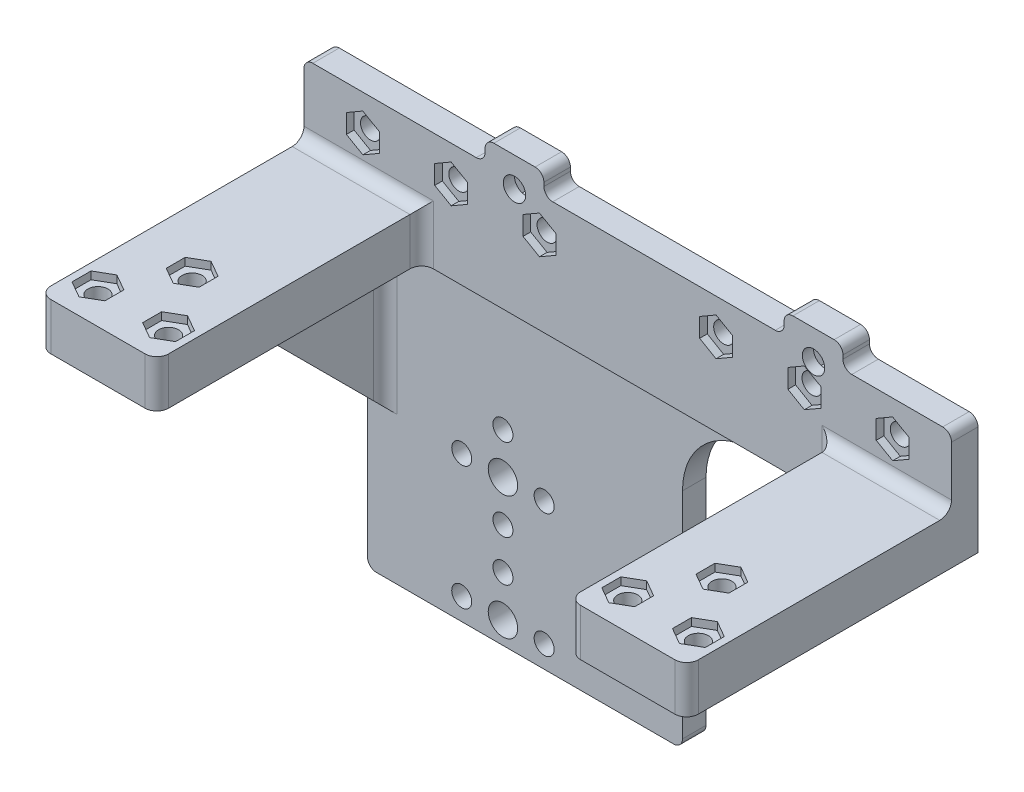
SolidWorks part; units mm, degrees
ref_plane "前视基准面" through (0, 0, 0) normal (0, 0, 1) x (1, 0, 0)
ref_plane "上视基准面" through (0, 0, 0) normal (0, 1, 0) x (1, 0, 0)
ref_plane "右视基准面" through (0, 0, 0) normal (1, 0, 0) x (0, 0, -1)
sketch "草图1" plane through (0, 0, 0) normal (0, 0, 1) x (1, 0, 0)
  line L6 (-55, 0) -> (55, 0)
  line L11 (55, 0) -> (55, 20)
  line L12 (55, 20) -> (-55, 20)
  line L13 (-55, 20) -> (-55, 0)
  line L14 (-45, 14) -> (45, 14) construction
  line L15 (0, 14) -> (0, 0) construction
  circle A6 centre (-45, 14) radius 1.7
  circle A7 centre (-30, 14) radius 1.7
  circle A8 centre (-15, 14) radius 1.7
  circle A9 centre (15, 14) radius 1.7
  circle A10 centre (30, 14) radius 1.7
  circle A11 centre (45, 14) radius 1.7
  dimension "D1" = 110
  dimension "D2" = 3.4
  dimension "D3" = 90
  dimension "D4" = 60
  dimension "D5" = 30
  dimension "D6" = 20
  dimension "D7" = 6
extrude "凸台-拉伸1" add sketch "草图1" along normal blind 4.5
sketch "草图2" plane through (0, 0, 4.5) normal (0, 0, 1) x (1, 0, 0)
  line L0 (0, 0) -> (0, 12.4325) construction
  line L1 (-55, 0) -> (-35, 0)
  line L2 (-55, 0) -> (-55, 8)
  line L3 (-55, 8) -> (-35, 8)
  line L4 (-35, 0) -> (-35, 8)
  line L5 (55, 0) -> (35, 0)
  line L6 (55, 0) -> (55, 8)
  line L7 (55, 8) -> (35, 8)
  line L8 (35, 0) -> (35, 8)
  dimension "D1" = 8
  dimension "D2" = 20
extrude "凸台-拉伸2" add sketch "草图2" along normal blind 45
sketch "草图3" plane through (0, 0, 4.5) normal (0, 0, 1) x (1, 0, 0)
  line L1 (-45, 17.22) -> (-47.7886, 15.61)
  line L2 (-47.7886, 15.61) -> (-47.7886, 12.39)
  line L3 (-47.7886, 12.39) -> (-45, 10.78)
  line L4 (-45, 10.78) -> (-42.2114, 12.39)
  line L5 (-42.2114, 12.39) -> (-42.2114, 15.61)
  line L6 (-42.2114, 15.61) -> (-45, 17.22)
  line L7 (-30, 17.22) -> (-32.7886, 15.61)
  line L8 (-32.7886, 15.61) -> (-32.7886, 12.39)
  line L9 (-32.7886, 12.39) -> (-30, 10.78)
  line L10 (-30, 10.78) -> (-27.2114, 12.39)
  line L11 (-27.2114, 12.39) -> (-27.2114, 15.61)
  line L12 (-27.2114, 15.61) -> (-30, 17.22)
  line L13 (-15, 17.22) -> (-17.7886, 15.61)
  line L14 (-17.7886, 15.61) -> (-17.7886, 12.39)
  line L15 (-17.7886, 12.39) -> (-15, 10.78)
  line L16 (-15, 10.78) -> (-12.2114, 12.39)
  line L17 (-12.2114, 12.39) -> (-12.2114, 15.61)
  line L18 (-12.2114, 15.61) -> (-15, 17.22)
  line L19 (15, 17.22) -> (12.2114, 15.61)
  line L20 (12.2114, 15.61) -> (12.2114, 12.39)
  line L21 (12.2114, 12.39) -> (15, 10.78)
  line L22 (15, 10.78) -> (17.7886, 12.39)
  line L23 (17.7886, 12.39) -> (17.7886, 15.61)
  line L24 (17.7886, 15.61) -> (15, 17.22)
  line L25 (30, 17.22) -> (27.2114, 15.61)
  line L26 (27.2114, 15.61) -> (27.2114, 12.39)
  line L27 (27.2114, 12.39) -> (30, 10.78)
  line L28 (30, 10.78) -> (32.7886, 12.39)
  line L29 (32.7886, 12.39) -> (32.7886, 15.61)
  line L30 (32.7886, 15.61) -> (30, 17.22)
  line L31 (45, 17.22) -> (42.2114, 15.61)
  line L32 (42.2114, 15.61) -> (42.2114, 12.39)
  line L33 (42.2114, 12.39) -> (45, 10.78)
  line L34 (45, 10.78) -> (47.7886, 12.39)
  line L35 (47.7886, 12.39) -> (47.7886, 15.61)
  line L36 (47.7886, 15.61) -> (45, 17.22)
  circle A0 centre (-45, 14) radius 2.7886 construction
  circle A1 centre (-30, 14) radius 2.7886 construction
  circle A2 centre (-15, 14) radius 2.7886 construction
  circle A3 centre (15, 14) radius 2.7886 construction
  circle A4 centre (30, 14) radius 2.7886 construction
  circle A5 centre (45, 14) radius 2.7886 construction
  dimension "D1" = 3.22
sketch "草图4" plane through (0, 0, 4.5) normal (0, 0, 1) x (1, 0, 0)
  line L1 (-24.2383, 13.6194) -> (-14.2383, 13.6194)
  line L2 (-24.2383, 13.6194) -> (-24.2383, 23.6194)
  line L3 (-24.2383, 23.6194) -> (-14.2383, 23.6194)
  line L4 (-14.2383, 13.6194) -> (-14.2383, 23.6194)
  line L5 (-24.2383, 13.6194) -> (-14.2383, 23.6194) construction
  line L6 (-24.2383, 23.6194) -> (-14.2383, 13.6194) construction
  line L7 (26.5617, 13.6194) -> (36.5617, 13.6194)
  line L8 (26.5617, 13.6194) -> (26.5617, 23.6194)
  line L9 (26.5617, 23.6194) -> (36.5617, 23.6194)
  line L10 (36.5617, 13.6194) -> (36.5617, 23.6194)
  line L11 (26.5617, 13.6194) -> (36.5617, 23.6194) construction
  line L12 (26.5617, 23.6194) -> (36.5617, 13.6194) construction
  point P0 (-19.2383, 18.6194)
  point P6 (31.5617, 18.6194)
  dimension "D1" = 10
extrude "凸台-拉伸3" add sketch "草图4" against normal up to surface (4.5 mm away) up to face at (0, 10, 0)
sketch "草图5" plane through (0, 0, 4.5) normal (0, 0, 1) x (1, 0, 0)
  circle A0 centre (-19.2383, 18.6194) radius 1.9
  circle A1 centre (31.5617, 18.6194) radius 1.9
  circle A2 centre (-15, 14) radius 1.7
  circle A3 centre (30, 14) radius 1.7
  dimension "D1" = 3.8
extrude "切除-拉伸1" cut sketch "草图5" against normal through all
extrude "切除-拉伸2" cut sketch "草图3" against normal blind 1.3
sketch "草图6" plane through (0, 0, 0) normal (0, 0, -1) x (-1, 0, 0)
  line L1 (-34.8617, 18.6194) -> (-33.2117, 15.7615)
  line L2 (-33.2117, 15.7615) -> (-29.9117, 15.7615)
  line L3 (-29.9117, 15.7615) -> (-28.2617, 18.6194)
  line L4 (-28.2617, 18.6194) -> (-29.9117, 21.4773)
  line L5 (-29.9117, 21.4773) -> (-33.2117, 21.4773)
  line L6 (-33.2117, 21.4773) -> (-34.8617, 18.6194)
  line L7 (15.9383, 18.6194) -> (17.5883, 15.7615)
  line L8 (17.5883, 15.7615) -> (20.8883, 15.7615)
  line L9 (20.8883, 15.7615) -> (22.5383, 18.6194)
  line L10 (22.5383, 18.6194) -> (20.8883, 21.4773)
  line L11 (20.8883, 21.4773) -> (17.5883, 21.4773)
  line L12 (17.5883, 21.4773) -> (15.9383, 18.6194)
  circle A0 centre (-31.5617, 18.6194) radius 2.8579 construction
  circle A1 centre (19.2383, 18.6194) radius 2.8579 construction
  dimension "D1" = 3.3
extrude "切除-拉伸3" cut sketch "草图6" against normal blind 2.6
sketch "草图7" plane through (0, 0, 0) normal (0, -1, 0) x (1, 0, 0)
  line L8 (-55, 0) -> (55, 0)
  line L9 (55, 0) -> (55, 49.5)
  line L10 (55, 49.5) -> (35, 49.5)
  line L11 (35, 49.5) -> (35, 4.5)
  line L12 (35, 4.5) -> (-35, 4.5)
  line L13 (-35, 4.5) -> (-35, 49.5)
  line L14 (-35, 49.5) -> (-55, 49.5)
  line L15 (-55, 49.5) -> (-55, 0)
  line L16 (-55, 0) -> (55, 0)
  line L17 (55, 0) -> (55, 49.5)
  line L18 (55, 49.5) -> (35, 49.5)
  line L19 (35, 49.5) -> (35, 4.5)
  line L20 (35, 4.5) -> (-35, 4.5)
  line L21 (-35, 4.5) -> (-35, 49.5)
  line L22 (-35, 49.5) -> (-55, 49.5)
  line L23 (-55, 49.5) -> (-55, 0)
  circle A0 centre (-51, 43.5) radius 1.7
  circle A1 centre (-39, 43.5) radius 1.7
  circle A2 centre (-45, 33.5) radius 1.7
  circle A3 centre (39, 43.5) radius 1.7
  circle A4 centre (51, 43.5) radius 1.7
  circle A5 centre (45, 33.5) radius 1.7
  dimension "D2" = 3.4
  dimension "D1" = 0
extrude "切除-拉伸5" cut sketch "草图7" against normal through all contours A0 | A1 | A2 | A4 | A3 | A5
sketch "草图8" plane through (0, 8, 0) normal (0, 1, 0) x (1, 0, 0)
  line L1 (51, -46.72) -> (53.7886, -45.11)
  line L2 (53.7886, -45.11) -> (53.7886, -41.89)
  line L3 (53.7886, -41.89) -> (51, -40.28)
  line L4 (51, -40.28) -> (48.2114, -41.89)
  line L5 (48.2114, -41.89) -> (48.2114, -45.11)
  line L6 (48.2114, -45.11) -> (51, -46.72)
  line L7 (39, -46.72) -> (41.7886, -45.11)
  line L8 (41.7886, -45.11) -> (41.7886, -41.89)
  line L9 (41.7886, -41.89) -> (39, -40.28)
  line L10 (39, -40.28) -> (36.2114, -41.89)
  line L11 (36.2114, -41.89) -> (36.2114, -45.11)
  line L12 (36.2114, -45.11) -> (39, -46.72)
  line L13 (45, -36.72) -> (47.7886, -35.11)
  line L14 (47.7886, -35.11) -> (47.7886, -31.89)
  line L15 (47.7886, -31.89) -> (45, -30.28)
  line L16 (45, -30.28) -> (42.2114, -31.89)
  line L17 (42.2114, -31.89) -> (42.2114, -35.11)
  line L18 (42.2114, -35.11) -> (45, -36.72)
  line L19 (-39, -46.72) -> (-36.2114, -45.11)
  line L20 (-36.2114, -45.11) -> (-36.2114, -41.89)
  line L21 (-36.2114, -41.89) -> (-39, -40.28)
  line L22 (-39, -40.28) -> (-41.7886, -41.89)
  line L23 (-41.7886, -41.89) -> (-41.7886, -45.11)
  line L24 (-41.7886, -45.11) -> (-39, -46.72)
  line L25 (-51, -46.72) -> (-48.2114, -45.11)
  line L26 (-48.2114, -45.11) -> (-48.2114, -41.89)
  line L27 (-48.2114, -41.89) -> (-51, -40.28)
  line L28 (-51, -40.28) -> (-53.7886, -41.89)
  line L29 (-53.7886, -41.89) -> (-53.7886, -45.11)
  line L30 (-53.7886, -45.11) -> (-51, -46.72)
  line L31 (-45, -36.72) -> (-42.2114, -35.11)
  line L32 (-42.2114, -35.11) -> (-42.2114, -31.89)
  line L33 (-42.2114, -31.89) -> (-45, -30.28)
  line L34 (-45, -30.28) -> (-47.7886, -31.89)
  line L35 (-47.7886, -31.89) -> (-47.7886, -35.11)
  line L36 (-47.7886, -35.11) -> (-45, -36.72)
  circle A0 centre (51, -43.5) radius 2.7886 construction
  circle A1 centre (39, -43.5) radius 2.7886 construction
  circle A2 centre (45, -33.5) radius 2.7886 construction
  circle A3 centre (-39, -43.5) radius 2.7886 construction
  circle A4 centre (-51, -43.5) radius 2.7886 construction
  circle A5 centre (-45, -33.5) radius 2.7886 construction
  dimension "D1" = 3.22
extrude "切除-拉伸6" cut sketch "草图8" against normal blind 1.3
sketch "草图9" plane through (0, 0, 0) normal (0, -1, 0) x (1, 0, 0)
  line L2 (-55, 0) -> (55, 0) construction
  line L3 (-55, 0) -> (55, 0)
  line L5 (-54, 4) -> (-54, 0)
  line L7 (26, 4) -> (26, 0)
  line L8 (0, 0) -> (0, 8.7602) construction
  line L9 (-54, 4) -> (26, 4)
  point P4 (26, 2)
  dimension "D1" = 80
  dimension "D2" = 4
  dimension "D3" = 54
extrude "凸台-拉伸4" add sketch "草图9" along normal blind 50 contours L9 L5 L3 L7 | L3 L8 L9 L5
sketch "草图11" plane through (0, 0, 0) normal (0, 0, -1) x (-1, 0, 0)
  line L0 (54, -50) -> (-26, -50) construction
  line L1 (54, -50) -> (-26, -50)
  line L2 (-26, -50) -> (-26, 0) construction
  line L3 (-26, -50) -> (-26, 0)
  line L4 (54, -50) -> (54, 0) construction
  line L5 (54, -50) -> (54, 0)
  line L6 (-8.8, -50) -> (-8.8, 0)
  line L7 (-8.8, 0) -> (-26, 0)
  line L8 (44.7, -50) -> (44.7, 0)
  line L9 (44.7, 0) -> (54, 0)
  line L10 (-26, 0) -> (-55, 0) construction
  line L11 (55, 0) -> (54, 0) construction
  line L22 (7.2, -64.75) -> (27.7, -64.75)
  line L23 (27.7, -64.75) -> (27.7, -56.75)
  line L24 (27.7, -56.75) -> (24.7, -56.75)
  line L25 (24.7, -56.75) -> (24.7, -54.75)
  line L26 (24.7, -54.75) -> (32.7, -54.75)
  line L27 (34.7, -52.75) -> (34.7, -18.75)
  line L28 (32.7, -16.75) -> (24.7, -16.75)
  line L29 (24.7, -16.75) -> (24.7, -14.75)
  line L30 (24.7, -14.75) -> (27.7, -14.75)
  line L31 (27.7, -14.75) -> (27.7, -6.75)
  line L32 (27.7, -6.75) -> (7.2, -6.75)
  line L33 (5.2, -8.75) -> (5.2, -14.75)
  line L34 (5.2, -14.75) -> (-0.8, -14.75)
  line L35 (-0.8, -14.75) -> (-0.8, -56.75)
  line L36 (-0.8, -56.75) -> (5.2, -56.75)
  line L37 (5.2, -56.75) -> (5.2, -62.75)
  line L38 (7.2, -64.75) -> (27.7, -64.75) construction
  line L39 (27.7, -64.75) -> (27.7, -56.75) construction
  line L40 (27.7, -56.75) -> (24.7, -56.75) construction
  line L41 (24.7, -56.75) -> (24.7, -54.75) construction
  line L42 (24.7, -54.75) -> (32.7, -54.75) construction
  line L43 (34.7, -52.75) -> (34.7, -18.75) construction
  line L44 (32.7, -16.75) -> (24.7, -16.75) construction
  line L45 (24.7, -16.75) -> (24.7, -14.75) construction
  line L46 (24.7, -14.75) -> (27.7, -14.75) construction
  line L47 (27.7, -14.75) -> (27.7, -6.75) construction
  line L48 (27.7, -6.75) -> (7.2, -6.75) construction
  line L49 (5.2, -8.75) -> (5.2, -14.75) construction
  line L50 (5.2, -14.75) -> (-0.8, -14.75) construction
  line L51 (-0.8, -14.75) -> (-0.8, -56.75) construction
  line L52 (-0.8, -56.75) -> (5.2, -56.75) construction
  line L53 (5.2, -56.75) -> (5.2, -62.75) construction
  circle A0 centre (21.7, -18.25) radius 1.7
  circle A1 centre (14.7, -25.25) radius 1.7
  circle A2 centre (21.7, -32.25) radius 1.7
  circle A3 centre (28.7, -25.25) radius 1.7
  arc A4 (32.7, -54.75) -> (34.7, -52.75) centre (32.7, -52.75) ccw
  arc A5 (34.7, -18.75) -> (32.7, -16.75) centre (32.7, -18.75) ccw
  arc A6 (7.2, -6.75) -> (5.2, -8.75) centre (7.2, -8.75) ccw
  arc A7 (5.2, -62.75) -> (7.2, -64.75) centre (7.2, -62.75) ccw
  arc A8 (32.7, -54.75) -> (34.7, -52.75) centre (32.7, -52.75) ccw construction
  arc A9 (34.7, -18.75) -> (32.7, -16.75) centre (32.7, -18.75) ccw construction
  arc A10 (7.2, -6.75) -> (5.2, -8.75) centre (7.2, -8.75) ccw construction
  arc A11 (5.2, -62.75) -> (7.2, -64.75) centre (7.2, -62.75) ccw construction
  circle A12 centre (21.7, -39.25) radius 1.7
  circle A13 centre (21.7, -46.25) radius 2.5
  circle A14 centre (21.7, -25.25) radius 2.5
  circle A15 centre (4.2, -35.75) radius 1.7
  circle A16 centre (28.7, -46.25) radius 1.7
  circle A17 centre (14.7, -46.25) radius 1.7
  circle A18 centre (21.7, -53.25) radius 1.7
  line M52 (-26, 0) -> (-26, -50)
  line M53 (-26, -50) -> (54, -50)
  line M54 (54, -50) -> (54, 0)
  dimension "D2" = 3.4
  dimension "D3" = 5
  dimension "D4" = 8
  dimension "D5" = 10
  dimension "D1" = 0
extrude "切除-拉伸7" cut sketch "草图11" against normal through all contours L6 L7 M52 M53 | L9 L8 M53 M54 | A13 | A17 | A16 | A12 | A2 | A1 | A0 | A3 | A14 | A15
sketch "草图12" plane through (-44.7, 0, 0) normal (-1, 0, 0) x (0, 0, 1)
  line L1 (4, -25) -> (29, 0)
  line L2 (4, 0) -> (4, -50) construction
  line L3 (49.5, 0) -> (0, 0) construction
  dimension "D1" = 25
  dimension "D2" = 25
rib "筋4" sketch "草图12" sketch "草图12" thickness 3 extrusion direction parallel to sketch draft on no parameters "D1"=3
fillet "圆角1" radius 2 7 edges at (-41.7, -12.5, 4) (-41.7, 0, 16.5) (35, 4, 4.5) (45, 8, 4.5) (-35, 4, 4.5) (-45, 8, 4.5) (-44.7, 0, 14.5)
fillet "圆角2" radius 1.5 12 edges at (-55, 20, 2.25) (-24.2383, 20, 2.25) (-24.2383, 23.6194, 2.25) (-14.2383, 23.6194, 2.25) (-14.2383, 20, 2.25) (26.5617, 20, 2.25) (26.5617, 23.6194, 2.25) (36.5617, 23.6194, 2.25) (36.5617, 20, 2.25) (55, 20, 2.25) (8.8, -50, 2) (-44.7, -50, 2)
fillet "圆角3" radius 2 4 edges at (-55, 4, 49.5) (-35, 4, 49.5) (55, 4, 49.5) (35, 4, 49.5)
fillet "圆角4" radius 12 1 edges at (8.8, 0, 2)
